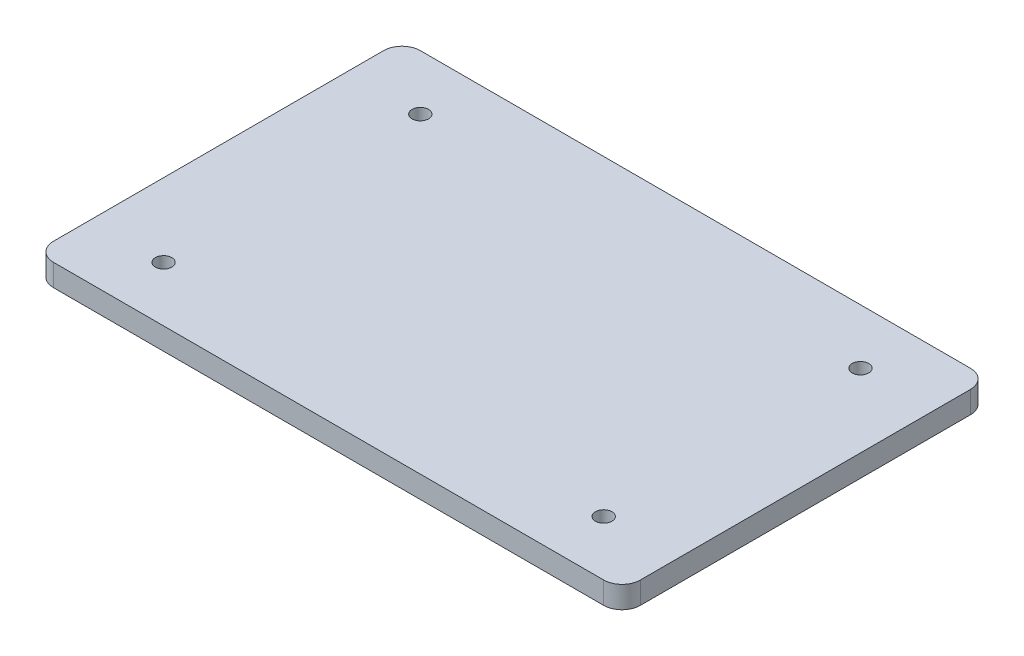
SolidWorks part; units mm, degrees
ref_plane "Front Plane" through (0, 0, 0) normal (0, 0, 1) x (1, 0, 0)
ref_plane "Top Plane" through (0, 0, 0) normal (0, 1, 0) x (1, 0, 0)
ref_plane "Right Plane" through (0, 0, 0) normal (1, 0, 0) x (0, 0, -1)
sketch "Sketch1" plane through (0, 0, 0) normal (0, 1, 0) x (1, 0, 0)
  line L1 (80, 50) -> (-80, 50)
  line L2 (80, 50) -> (80, -50)
  line L3 (80, -50) -> (-80, -50)
  line L4 (-80, 50) -> (-80, -50)
  line L5 (80, 50) -> (-80, -50) construction
  line L6 (80, -50) -> (-80, 50) construction
  point P0 (0, 0)
  dimension "D1" = 160
  dimension "D2" = 100
extrude "BasePlate_160x100x6" add sketch "Sketch1" along normal blind 6
fillet "Corner_Fillet_R5" radius 5 4 edges at (80, 3, -50) (-80, 3, -50) (80, 3, 50) (-80, 3, 50)
hole_wizard "M4_Isolator_Clearance_Holes" positions "Sketch2" profile "Sketch3" hole size "Ø4.5" standard "ISO" end condition through all
sketch "Sketch2" plane through (0, 6, 0) normal (0, 1, 0) x (1, 0, 0)
  point P0 (-60, 35)
  point P2 (60, 35)
  point P4 (60, -35)
  point P6 (-60, -35)
  point P9 (0, 0)
  point P10 (0, 0)
  point P11 (0, 0)
  point P12 (0, 0)
  point P13 (0, 0)
  point P14 (0, 0)
  point P15 (0, 0)
  dimension "D1" = 60
  dimension "D2" = 35
  dimension "D3" = 60
  dimension "D4" = 35
  dimension "D5" = 35
  dimension "D6" = 60
  dimension "D7" = 60
  dimension "D8" = 35
sketch "Sketch3" plane through (-60, 6, -35) normal (1, 0, 0) x (0, 0, 1)
  line L0 (0, 0) -> (0, 6)
  line L1 (0, 6) -> (2.25, 6)
  line L2 (2.25, 6) -> (2.25, 0)
  line L5 (2.25, 0) -> (0, 0)
  line L11 (0, -6.35) -> (0, 107.95) construction
  dimension "Thru Hole Dia." = 4.5
  dimension "Thru Hole Depth" = 6
